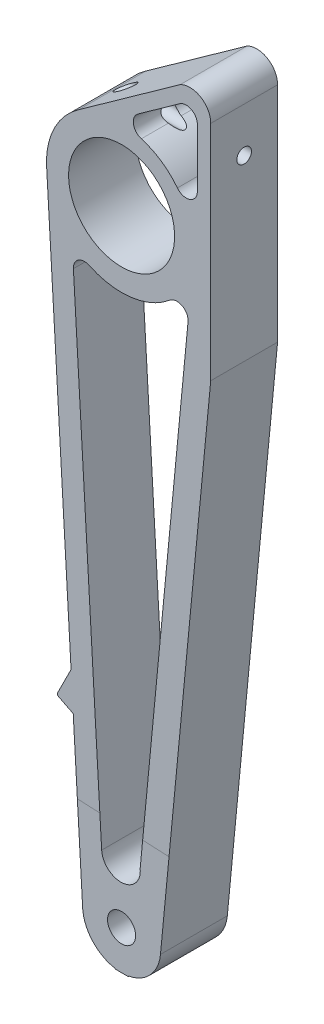
SolidWorks part; units mm, degrees
ref_plane "Front Plane" through (0, 0, 0) normal (0, 0, 1) x (1, 0, 0)
ref_plane "Top Plane" through (0, 0, 0) normal (0, 1, 0) x (1, 0, 0)
ref_plane "Right Plane" through (0, 0, 0) normal (1, 0, 0) x (0, 0, -1)
sketch "Sketch1" plane through (0, 0, 0) normal (0, 0, 1) x (1, 0, 0)
  line L0 (-25.4, 124.0003) -> (-25.4, 104.9503) construction
  line L1 (-25.4, -124.0003) -> (25.4, -124.0003)
  line L2 (-25.4, -124.0003) -> (-25.4, 124.0003)
  line L3 (-25.4, 124.0003) -> (25.4, 124.0003)
  line L4 (25.4, -124.0003) -> (25.4, 124.0003)
  line L5 (-25.4, -124.0003) -> (25.4, 124.0003) construction
  line L6 (-25.4, 124.0003) -> (25.4, -124.0003) construction
  line L7 (-25.4, 104.9503) -> (-25.4, 54.1503)
  line L8 (-25.4, 54.1503) -> (25.4, 54.1503) construction
  line L9 (-25.4, 104.9503) -> (25.4, 104.9503) construction
  line L10 (0, 104.9503) -> (0, 54.1503) construction
  line L11 (0, 79.5503) -> (-25.4, 79.5503) construction
  line L12 (0, -124.0003) -> (0, -98.6003) construction
  circle A0 centre (0, 79.5503) radius 15.113
  circle A1 centre (0, -98.6003) radius 4
  point P0 (0, 0)
  dimension "D5" = 30.226
  dimension "D7" = 8
  dimension "D1" = 248.0005
  dimension "D2" = 50.8
  dimension "D3" = 19.05
  dimension "D4" = 50.8
  dimension "D6" = 25.4
extrude "Boss-Extrude1" add sketch "Sketch1" along normal blind 19.05 contours L1 L4 L3 L2 A1 A0
sketch "Sketch2" plane through (25.4, 0, 0) normal (1, 0, 0) x (0, 0, -1)
  line L0 (-19.05, -124.0003) -> (-19.05, 124.0003) construction
  line L1 (-19.05, 112.5703) -> (0, 112.5703)
  line L2 (-19.05, 112.5703) -> (-19.05, 49.0703)
  line L3 (-19.05, 49.0703) -> (0, 49.0703)
  line L4 (0, 112.5703) -> (0, 49.0703)
  line L5 (-19.05, 124.0003) -> (0, 124.0003) construction
  line L6 (0, -124.0003) -> (0, 124.0003) construction
  dimension "D1" = 11.43
  dimension "D2" = 63.5
sketch "Sketch3" plane through (25.4, 0, 0) normal (1, 0, 0) x (0, 0, -1)
  line L0 (-9.525, 124.0003) -> (-9.525, 99.8703) construction
  line L1 (-19.05, 124.0003) -> (0, 124.0003) construction
  circle A0 centre (-9.525, 99.8703) radius 2.0828
  dimension "D2" = 4.1656
  dimension "D1" = 24.13
extrude "Cut-Extrude1" cut sketch "Sketch3" against normal up to next
sketch "Sketch4" plane through (0, 0, 19.05) normal (0, 0, 1) x (1, 0, 0)
  line L0 (25.4, 112.5703) -> (25.4, 49.0703)
  line L2 (-21.4198, 79.5503) -> (-11.1296, -98.6003)
  line L3 (-5.6793, -82.3105) -> (-14.0922, 63.419)
  line L5 (5.2925, -81.3598) -> (20.061, 72.0426)
  line L6 (25.4, 124.0003) -> (-12.7187, 96.7852) construction
  line L8 (25.4, 49.0703) -> (11.0784, -99.667)
  line L10 (-12.7187, 96.7852) -> (16.7257, 117.8072)
  arc A0 (-14.0922, 63.419) -> (20.061, 72.0426) centre (0, 79.5503) ccw
  arc A3 (-11.1296, -98.6003) -> (11.0784, -99.667) centre (0, -98.6003) ccw
  arc A4 (-12.1706, 97.1765) -> (-21.2773, 77.084) centre (0, 79.5503) ccw
  arc A5 (5.2925, -81.3598) -> (-5.6793, -82.3105) centre (-0.1822, -81.9637) cw
  arc A6 (20.061, 72.0426) -> (-14.0922, 63.419) centre (0, 79.5503) cw
  arc A8 (25.4, 112.5703) -> (16.7257, 117.8072) centre (19.482, 112.5703) ccw
  line M8 (-25.4, -124.0003) -> (25.4, -124.0003)
  line M9 (25.4, -124.0003) -> (25.4, 124.0003)
  line M10 (25.4, 124.0003) -> (-25.4, 124.0003)
  line M11 (-25.4, 124.0003) -> (-25.4, -124.0003)
  dimension "D2" = 36.1787
extrude "Cut-Extrude2" cut sketch "Sketch4" against normal up to next contours L6 L8 A3 L2 A4 L10 M10 M11 M8 M9 | L6 A8 M9 | A5 L5 A0 L3
fillet "Fillet2" radius 3.175 1 edges at (-14.0922, 63.419, 9.525)
fillet "Fillet3" radius 3.175 1 edges at (20.061, 72.0426, 9.525)
sketch "Sketch8" plane through (0, 0, 0) normal (0, 1, 0) x (1, 0, 0)
  line L0 (0, 0) -> (0, -19.05) construction
  line L1 (16.7257, -19.05) -> (-12.1706, -19.05) construction
  circle A0 centre (0, -9.525) radius 1.5
  dimension "D1" = 3
extrude "Cut-Extrude3" cut sketch "Sketch8" against normal up to surface (109.7299 mm away)
sketch "Sketch9" plane through (0, 0, 19.05) normal (0, 0, 1) x (1, 0, 0)
  line L0 (21.6369, 116.6321) -> (21.59, 116.5987)
  line L1 (16.7257, 117.8072) -> (-12.1706, 97.1765) construction
  line L2 (21.59, 93.838) -> (21.59, 110.4307)
  line L3 (25.4, 112.5703) -> (25.4, 49.0703) construction
  line L4 (16.5701, 113.0147) -> (4.6645, 104.5146)
  line L5 (21.59, 116.5987) -> (21.59, 117.6593)
  arc A0 (4.6645, 104.5146) -> (5.6226, 98.8819) centre (6.5093, 101.9306) ccw
  arc A1 (15.9065, 91.8917) -> (5.6226, 98.8819) centre (0, 79.5503) ccw
  arc A2 (15.9065, 91.8917) -> (21.59, 93.838) centre (18.415, 93.838) ccw
  arc A3 (21.59, 110.4307) -> (16.5701, 113.0147) centre (18.415, 110.4307) ccw
  dimension "D1" = 3.81
  dimension "D3" = 6.35
  dimension "D4" = 6.35
  dimension "D5" = 6.35
  dimension "D2" = 3.81
extrude "Cut-Extrude4" cut sketch "Sketch9" against normal up to next contours L2 A3 L4 A0 A1 A2
ref_plane "Plane1" through (-4.7508, -98.9067, 0) normal (0.048, 0.9988, 0) x (0.9988, -0.048, 0)
ref_plane "Plane2" through (-3.5321, -73.5359, 0) normal (0.048, 0.9988, 0) x (0.9988, -0.048, 0)
split line "Split Line2"
sketch "Sketch10" plane through (25.4, 0, 0) normal (1, 0, 0) x (0, 0, -1)
  line L0 (-15.6025, 107.6332) -> (-13.0945, 106.3471) construction
sketch "Sketch12" plane through (0, 0, 19.05) normal (0, 0, 1) x (1, 0, 0)
  line L0 (0, -102.6003) -> (0, -103.0103) construction
  line L2 (1.905, -103.0103) -> (-1.905, -103.0103)
  line L3 (1.905, -103.0103) -> (1.905, -109.7299)
  line L4 (1.905, -109.7299) -> (-1.905, -109.7299)
  line L5 (-1.905, -103.0103) -> (-1.905, -109.7299)
  arc A4 (-1.5, -102.3084) -> (1.5, -102.3084) centre (0, -98.6003) ccw construction
  point P2 (0, -103.0103)
  dimension "D1" = 3.81
extrude "Boss-Extrude3" add sketch "Sketch12" against normal up to surface (19.05 mm away) up to face at (0.0327, -84.1242, 0)
sketch "Sketch14" plane through (0, 0, 0) normal (0, 1, 0) x (1, 0, 0)
  line L0 (-12.1706, 0) -> (16.7257, 0) construction
  circle A0 centre (0, -9.525) radius 1.5
  dimension "D1" = 9.525
extrude "Cut-Extrude5" cut sketch "Sketch14" against normal up to surface (109.7299 mm away) up to face at (0, -109.7299, 9.525)
sketch "Sketch17" plane through (0, 0, 19.05) normal (0, 0, 1) x (1, 0, 0)
  line L0 (-12.6025, -73.1002) -> (-14.3924, -42.1122) construction
  line L1 (-21.2773, 77.084) -> (-12.6025, -73.1002) construction
  line L2 (-14.3924, -42.1122) -> (-13.7827, -52.6679)
  line L3 (-18.5059, -50.293) -> (-13.7827, -52.6679)
  line L5 (6.0017, -73.9938) -> (-6.1932, -73.4081) construction
  line L6 (-14.3924, -42.1122) -> (-18.5059, -50.293)
  dimension "D1" = 30
  dimension "D2" = 30.988
  dimension "D4" = 9.1567
extrude "Boss-Extrude5" add sketch "Sketch17" against normal up to surface (19.05 mm away) up to face at (15.113, 79.5503, 0)
fillet "Fillet4" radius 0.635 1 edges at (-18.5059, -50.293, 9.525)
sketch "Sketch11" plane through (0, 0, 19.05) normal (0, 0, 1) x (1, 0, 0)
  line L0 (5.2925, -81.3598) -> (6.0017, -73.9938) construction
  line L1 (-5.6793, -82.3105) -> (-6.1932, -73.4081) construction
  line L2 (-6.1932, -73.4081) -> (-13.7306, 57.1553) construction
  line L3 (6.0017, -73.9938) -> (18.9381, 60.3789) construction
  line L4 (5.2925, -81.3598) -> (6.0017, -73.9938)
  line L5 (-5.6793, -82.3105) -> (-6.1932, -73.4081)
  line L6 (-6.1932, -73.4081) -> (-13.7306, 57.1553)
  line L7 (6.0017, -73.9938) -> (18.9381, 60.3789)
  line L8 (21.59, 93.838) -> (21.59, 110.4307) construction
  line L9 (16.5701, 113.0147) -> (4.6645, 104.5146) construction
  line L10 (21.59, 93.838) -> (21.59, 110.4307)
  line L11 (16.5701, 113.0147) -> (4.6645, 104.5146)
  arc A0 (-5.6793, -82.3105) -> (5.2925, -81.3598) centre (-0.1822, -81.9637) ccw construction
  arc A1 (-9.1976, 60.2057) -> (-13.7306, 57.1553) centre (-10.5609, 57.3383) ccw construction
  arc A2 (-9.1976, 60.2057) -> (13.7409, 63.1187) centre (0, 79.5503) ccw construction
  arc A3 (18.9381, 60.3789) -> (13.7409, 63.1187) centre (15.7777, 60.6831) ccw construction
  arc A4 (-5.6793, -82.3105) -> (5.2925, -81.3598) centre (-0.1822, -81.9637) ccw
  arc A5 (-9.1976, 60.2057) -> (-13.7306, 57.1553) centre (-10.5609, 57.3383) ccw
  arc A6 (-9.1976, 60.2057) -> (13.7409, 63.1187) centre (0, 79.5503) ccw
  arc A7 (18.9381, 60.3789) -> (13.7409, 63.1187) centre (15.7777, 60.6831) ccw
  arc A8 (15.9065, 91.8917) -> (21.59, 93.838) centre (18.415, 93.838) ccw construction
  arc A9 (15.9065, 91.8917) -> (5.6226, 98.8819) centre (0, 79.5503) ccw construction
  arc A10 (21.59, 110.4307) -> (16.5701, 113.0147) centre (18.415, 110.4307) ccw construction
  arc A11 (4.6645, 104.5146) -> (5.6226, 98.8819) centre (6.5093, 101.9306) ccw construction
  arc A12 (15.9065, 91.8917) -> (21.59, 93.838) centre (18.415, 93.838) ccw
  arc A13 (15.9065, 91.8917) -> (5.6226, 98.8819) centre (0, 79.5503) ccw
  arc A14 (21.59, 110.4307) -> (16.5701, 113.0147) centre (18.415, 110.4307) ccw
  arc A15 (4.6645, 104.5146) -> (5.6226, 98.8819) centre (6.5093, 101.9306) ccw
extrude "Boss-Extrude2" [suppressed] add sketch "Sketch11" against normal up to surface (19.05 mm away)
